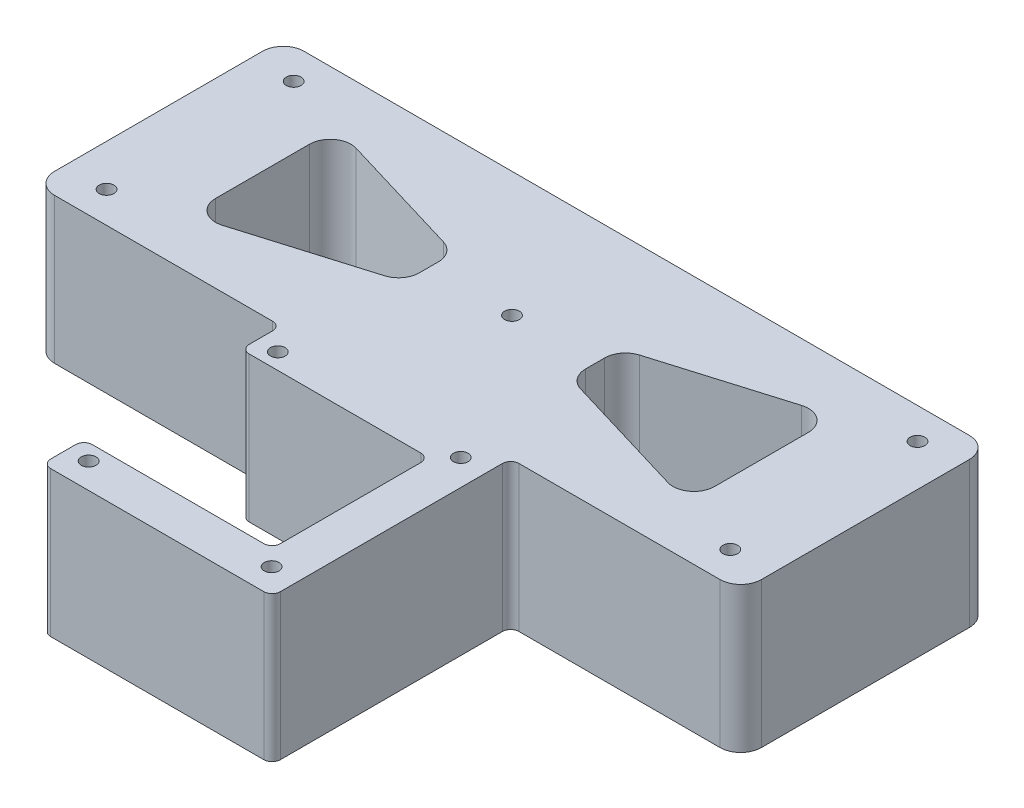
SolidWorks part; units mm, degrees
ref_plane "Front Plane" through (0, 0, 0) normal (0, 0, 1) x (1, 0, 0)
ref_plane "Top Plane" through (0, 0, 0) normal (0, 1, 0) x (1, 0, 0)
ref_plane "Right Plane" through (0, 0, 0) normal (1, 0, 0) x (0, 0, -1)
sketch "Sketch1" plane through (0, 0, 0) normal (0, 1, 0) x (1, 0, 0)
  line L1 (-95.25, -28.575) -> (95.25, -28.575) construction
  line L2 (-95.25, -28.575) -> (-95.25, 28.575) construction
  line L3 (-95.25, 28.575) -> (95.25, 28.575) construction
  line L4 (95.25, -28.575) -> (95.25, 28.575) construction
  line L5 (-95.25, -28.575) -> (95.25, 28.575) construction
  line L6 (-95.25, 28.575) -> (95.25, -28.575) construction
  line L7 (107.95, -38.1) -> (-107.95, -38.1)
  line L8 (107.95, -38.1) -> (107.95, 38.1)
  line L9 (107.95, 38.1) -> (-107.95, 38.1)
  line L10 (-107.95, -38.1) -> (-107.95, 38.1)
  line L11 (107.95, -38.1) -> (-107.95, 38.1) construction
  line L12 (107.95, 38.1) -> (-107.95, -38.1) construction
  line L14 (-76.2, 22.86) -> (-76.2, -22.86)
  line L15 (-76.2, -22.86) -> (-25.4, -7.62)
  line L16 (-25.4, -7.62) -> (-25.4, 7.62)
  line L17 (-25.4, 7.62) -> (-76.2, 22.86)
  line L18 (25.4, 7.62) -> (25.4, -7.62)
  line L19 (25.4, -7.62) -> (76.2, -22.86)
  line L20 (76.2, -22.86) -> (76.2, 22.86)
  line L21 (76.2, 22.86) -> (25.4, 7.62)
  line L22 (-32.4637, -38.1) -> (-32.4637, -50.3274)
  line L23 (-26.1137, -103.1875) -> (29.7663, -103.1875) construction
  line L24 (-26.1137, -103.1875) -> (-26.1137, -45.4025) construction
  line L25 (-26.1137, -45.4025) -> (29.7663, -45.4025) construction
  line L26 (29.7663, -103.1875) -> (29.7663, -45.4025) construction
  line L27 (-26.1137, -103.1875) -> (29.7663, -45.4025) construction
  line L28 (-26.1137, -45.4025) -> (29.7663, -103.1875) construction
  line L29 (-32.4637, -50.3274) -> (25.0038, -50.3274)
  line L30 (25.0038, -50.3274) -> (25.0038, -98.2626)
  line L31 (25.0038, -98.2626) -> (-32.4637, -98.2626)
  line L32 (-32.4637, -98.2626) -> (-32.4637, -110.9626)
  line L33 (-32.4637, -110.9626) -> (37.7038, -110.9626)
  line L34 (37.7038, -110.9626) -> (37.7038, -38.1)
  point P0 (0, 0)
  point P6 (0, 0)
  point P25 (1.8263, -74.295)
  dimension "D1" = 57.15
  dimension "D2" = 190.5
  dimension "D5" = 9.525
  dimension "D6" = 12.7
  dimension "D8" = 19.05
  dimension "D9" = 25.4
  dimension "D10" = 25.4
  dimension "D11" = 19.05
  dimension "D12" = 57.785
  dimension "D13" = 55.88
  dimension "D14" = 69.1363
  dimension "D15" = 16.8275
  dimension "D16" = 6.35
  dimension "D17" = 4.7625
  dimension "D18" = 12.7
  dimension "D19" = 12.7
extrude "Boss-Extrude1" add sketch "Sketch1" along normal blind 44.45
fillet "Fillet1" radius 6.35 12 edges at (-107.95, 22.225, -38.1) (-107.95, 22.225, 38.1) (107.95, 22.225, 38.1) (25.4, 22.225, 7.62) (76.2, 22.225, 22.86) (76.2, 22.225, -22.86) (25.4, 22.225, -7.62) (-76.2, 22.225, 22.86) (-25.4, 22.225, -7.62) (-25.4, 22.225, 7.62) (-76.2, 22.225, -22.86) (107.95, 22.225, -38.1)
hole_wizard "#8 Clearance Hole1" positions "Sketch2" profile "Sketch3" hole size "#8" standard "ANSI Inch" end condition through all
sketch "Sketch2" plane through (0, 44.45, 0) normal (0, 1, 0) x (1, 0, 0)
  line L0 (-95.25, 28.575) -> (95.25, -28.575) construction
  point P3 (95.25, 28.575)
  point P6 (95.25, -28.575)
  point P9 (-95.25, 28.575)
  point P12 (-95.25, -28.575)
  point P16 (0, 0)
  point P20 (-26.1137, -45.4025)
  point P23 (29.7663, -45.4025)
  point P26 (29.7663, -103.1875)
  point P29 (-26.1137, -103.1875)
sketch "Sketch3" plane through (95.25, 44.45, -28.575) normal (1, 0, 0) x (0, 0, 1)
  line L0 (0, 0) -> (0, 44.45)
  line L1 (0, 44.45) -> (2.2479, 44.45)
  line L2 (2.2479, 44.45) -> (2.2479, 0)
  line L5 (2.2479, 0) -> (0, 0)
  line L11 (0, -6.35) -> (0, 107.95) construction
  dimension "Thru Hole Dia." = 4.4958
  dimension "Thru Hole Depth" = 44.45
fillet "Fillet2" radius 2.54 8 edges at (37.7038, 22.225, 38.1) (37.7038, 22.225, 110.9626) (-32.4637, 22.225, 110.9626) (-32.4637, 22.225, 98.2626) (25.0038, 22.225, 50.3274) (-32.4637, 22.225, 38.1) (-32.4637, 22.225, 50.3274) (25.0038, 22.225, 98.2626)
